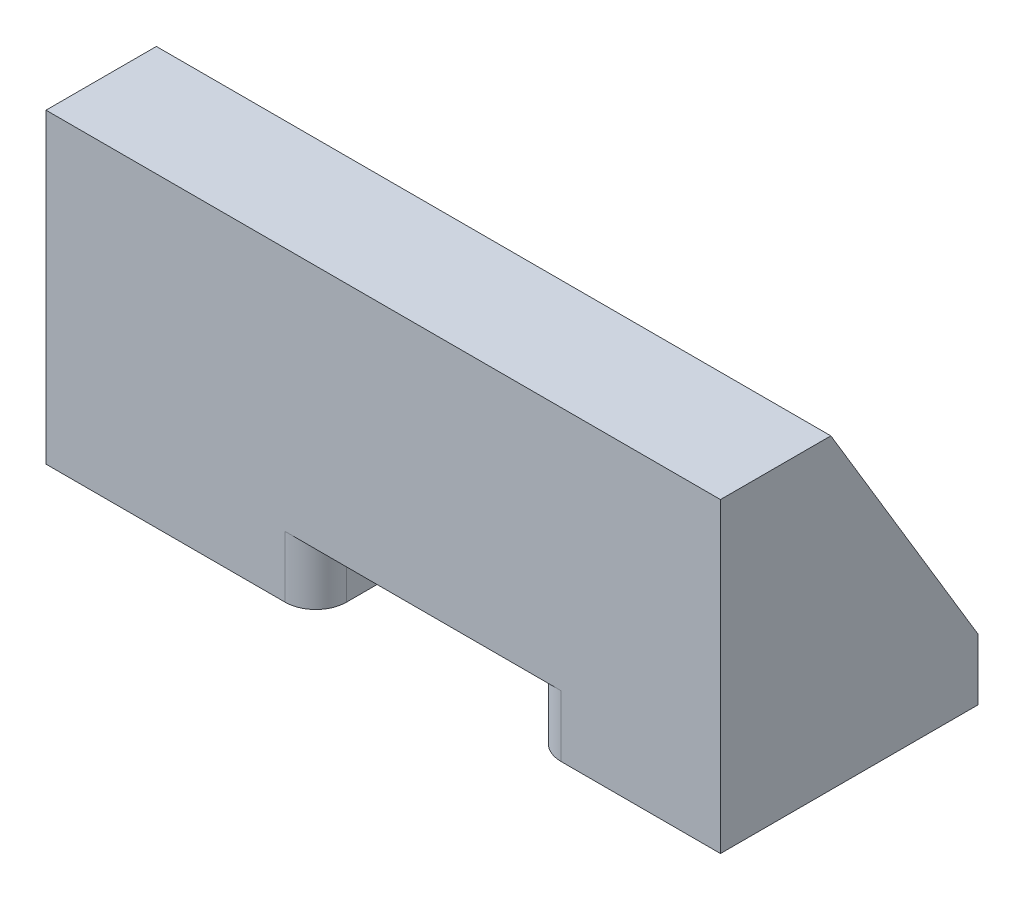
SolidWorks part; units mm, degrees
material "ABS"
ref_plane "Front" through (0, 0, 0) normal (0, 0, 1) x (1, 0, 0)
ref_plane "Top" through (0, 0, 0) normal (0, 1, 0) x (1, 0, 0)
ref_plane "Right" through (0, 0, 0) normal (1, 0, 0) x (0, 0, -1)
sketch "Sketch1" plane through (0, 0, 0) normal (0, 1, 0) x (1, 0, 0)
  line L1 (-55, -21) -> (55, -21)
  line L2 (-55, -21) -> (-55, 21)
  line L3 (-55, 21) -> (55, 21)
  line L4 (55, -21) -> (55, 21)
  line L5 (-55, -21) -> (55, 21) construction
  line L6 (-55, 21) -> (55, -21) construction
  point P0 (0, 0)
  dimension "D1" = 110
  dimension "D2" = 42
extrude "Boss-Extrude1" add sketch "Sketch1" along normal blind 10
hole_wizard "CBORE for M3 SBHCS1" positions "Sketch3" profile "Sketch2" counterbore size "M3" standard "ANSI Metric" end condition through all
sketch "Sketch3" plane through (0, 10, 0) normal (0, 1, 0) x (1, 0, 0)
  line L0 (-55, 8) -> (-45, 8) construction
  line L1 (-55, 21) -> (-55, -21) construction
  line L2 (-45, 8) -> (55, 8) construction
  line L3 (55, -21) -> (55, 21) construction
  line L5 (-55, -21) -> (55, -21) construction
  point P0 (-45, 8)
  point P2 (-32, 3)
  point P4 (32, 3)
  point P6 (45, 8)
  dimension "D1" = 90
  dimension "D2" = 29
  dimension "D3" = 13
  dimension "D4" = 5
  dimension "D5" = 13
  dimension "D6" = 5
  dimension "D7" = 10
sketch "Sketch2" plane through (-45, 10, -8) normal (1, 0, 0) x (0, 0, 1)
  line L0 (0, 0) -> (0, 10)
  line L1 (0, 10) -> (1.7, 10)
  line L3 (1.7, 10) -> (1.7, 5)
  line L4 (1.7, 5) -> (4, 5)
  line L5 (4, 5) -> (4, 0)
  line L7 (4, 0) -> (0, 0)
  line L11 (0, -6.35) -> (0, 107.95) construction
  dimension "Thru Hole Dia." = 3.4
  dimension "Thru Hole Depth" = 10
  dimension "C'Bore Dia." = 8
  dimension "C'Bore Depth" = 5
sketch "Sketch4" plane through (0, 10, 0) normal (0, 1, 0) x (1, 0, 0)
  line L3 (-55, -21) -> (55, -21) construction
  line L11 (24, -21) -> (24, 6)
  line L12 (19, 11) -> (-6, 11)
  line L13 (-11, 6) -> (-11, -21)
  line L14 (-11, -21) -> (24, -21)
  arc A0 (-6, 11) -> (-11, 6) centre (-6, 6) ccw
  arc A1 (19, 11) -> (24, 6) centre (19, 6) cw
  circle A2 centre (-32, 3) radius 1.7 construction
  point P11 (24, 11)
  dimension "D1" = 21
  dimension "D5" = 5
  dimension "D2" = 5
  dimension "D4" = 32
  dimension "D6" = 35
extrude "Cut-Extrude1" cut sketch "Sketch4" against normal up to surface (10 mm away) up to face at (-45, 0, -6.3)
fillet "Fillet2" radius 5 2 edges at (24, 5, 21) (-11, 5, 21)
sketch "Sketch6" plane through (0, 10, 0) normal (0, 1, 0) x (1, 0, 0)
  line L0 (55, -21) -> (55, 21) construction
  line L1 (-55, -21) -> (55, -21)
  line L2 (-55, -21) -> (-55, -3)
  line L3 (-55, -3) -> (55, -3)
  line L4 (55, -21) -> (55, -3)
  dimension "D1" = 18
extrude "Boss-Extrude2" add sketch "Sketch6" along normal blind 40
sketch "Sketch8" plane through (-55, 0, 0) normal (-1, 0, 0) x (0, 0, 1)
  line L0 (-21, 10) -> (3, 10)
  line L1 (3, 10) -> (3, 50)
  line L2 (3, 50) -> (-21, 10)
extrude "Boss-Extrude3" add sketch "Sketch8" against normal blind 5
sketch "Sketch9" plane through (55, 0, 0) normal (1, 0, 0) x (0, 0, -1)
  line L0 (-3, 10) -> (21, 10)
  line L1 (21, 10) -> (-3, 50)
  line L2 (-3, 50) -> (-3, 10)
extrude "Boss-Extrude4" add sketch "Sketch9" against normal blind 5
sketch "Sketch10" plane through (0, 10, 0) normal (0, -1, 0) x (1, 0, 0)
  line L1 (24, 3) -> (-11, 3)
  line L2 (24, 3) -> (24, 16)
  line L3 (24, 16) -> (-11, 16)
  line L4 (-11, 3) -> (-11, 16)
extrude "Cut-Extrude2" cut sketch "Sketch10" against normal blind 15
fillet "Fillet3" radius 5 3 edges at (24, 17.5, 3) (6.5, 25, 3) (-11, 17.5, 3)
